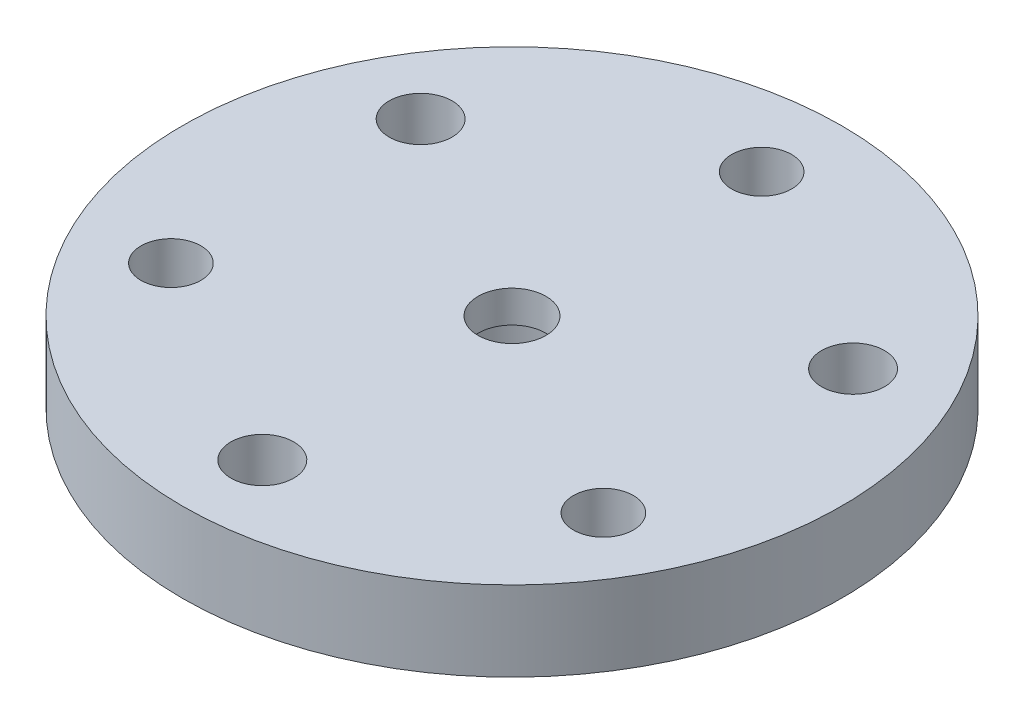
SolidWorks part; units mm, degrees
ref_plane "Front Plane" through (0, 0, 0) normal (0, 0, 1) x (1, 0, 0)
ref_plane "Top Plane" through (0, 0, 0) normal (0, 1, 0) x (1, 0, 0)
ref_plane "Right Plane" through (0, 0, 0) normal (1, 0, 0) x (0, 0, -1)
sketch "Sketch1" plane through (0, 0, 0) normal (0, 1, 0) x (1, 0, 0)
  circle A0 centre (0, 0) radius 16.5
  dimension "D1" = 33
extrude "Boss-Extrude1" add sketch "Sketch1" along normal blind 4
hole_wizard "CBORE for M3 Hex Socket Thin Head Cap Screw1" positions "Sketch13" profile "Sketch3" counterbore size "M3" standard "DIN" end condition through all
sketch "Sketch13" plane through (0, 0, 0) normal (0, 1, 0) x (1, 0, 0)
  point P0 (0, 0)
sketch "Sketch3" plane through (0, 0, 0) normal (1, 0, 0) x (0, 0, -1)
  line L0 (0, 0) -> (0, 4)
  line L1 (0, 4) -> (1.7, 4)
  line L3 (1.7, 4) -> (1.7, 2.4)
  line L4 (1.7, 2.4) -> (3.25, 2.4)
  line L5 (3.25, 2.4) -> (3.25, 0)
  line L7 (3.25, 0) -> (0, 0)
  line L11 (0, -6.35) -> (0, 107.95) construction
  dimension "Thru Hole Dia." = 3.4
  dimension "Thru Hole Depth" = 4
  dimension "C'Bore Dia." = 6.5
  dimension "C'Bore Depth" = 2.4
hole_wizard "Ø3.0mm Dowel Hole1" positions "Sketch8" profile "Sketch7" hole size "Ø3.0" standard "DIN"
sketch "Sketch8" plane through (0, 0, 0) normal (0, -1, 0) x (-1, 0, 0)
  circle A0 centre (0, 0) radius 12.5
  point P5 (0, 12.5)
  point P11 (10.8253, -6.25)
  point P12 (-10.8253, -6.25)
  dimension "D1" = 25
  dimension "D2" = 3
sketch "Sketch7" plane through (10.8253, 0, 6.25) normal (1, 0, 0) x (0, 0, -1)
  line L0 (0, 0) -> (0, 6.9013)
  line L1 (0, 6.9013) -> (1.5, 6)
  line L2 (1.5, 6) -> (1.5, 0)
  line L5 (1.5, 0) -> (0, 0)
  line L10 (0, 6.9013) -> (-1.5, 6) construction
  line L11 (0, -6.35) -> (0, 107.95) construction
  dimension "Hole Dia." = 3
  dimension "Hole Depth" = 6
  dimension "Drill Angle" = 118
hole_wizard "Tap Drill for M3 Helicoil1" positions "Sketch12" profile "Sketch11" hole size "M3x0.5" standard "DIN" end condition through all
sketch "Sketch12" plane through (0, 0, 0) normal (0, -1, 0) x (-1, 0, 0)
  circle A0 centre (0, 0) radius 12.5
  point P6 (0, -12.5)
  point P11 (-10.8253, 6.25)
  point P12 (10.8253, 6.25)
  dimension "D1" = 3
sketch "Sketch11" plane through (-10.8253, 0, -6.25) normal (1, 0, 0) x (0, 0, -1)
  line L0 (0, 0) -> (0, 4)
  line L1 (0, 4) -> (1.575, 4)
  line L2 (1.575, 4) -> (1.575, 0)
  line L5 (1.575, 0) -> (0, 0)
  line L11 (0, -6.35) -> (0, 107.95) construction
  dimension "Thru Hole Dia." = 3.15
  dimension "Thru Hole Depth" = 4
